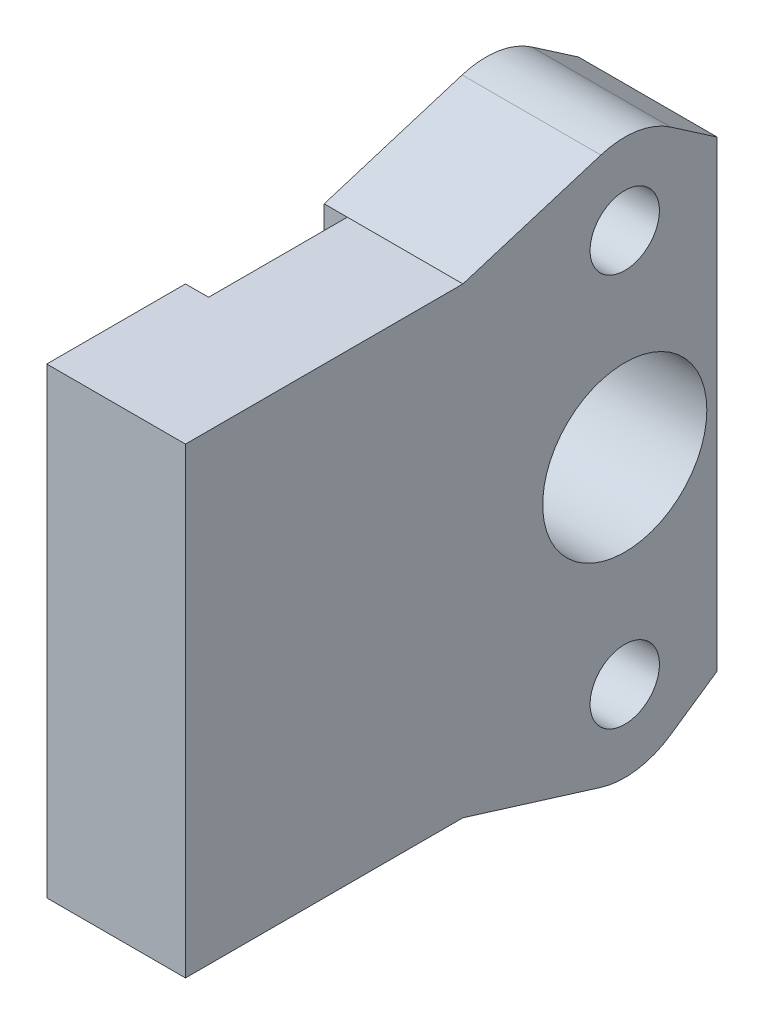
SolidWorks part; units mm, degrees
ref_plane "Front Plane" through (0, 0, 0) normal (0, 0, 1) x (1, 0, 0)
ref_plane "Top Plane" through (0, 0, 0) normal (0, 1, 0) x (1, 0, 0)
ref_plane "Right Plane" through (0, 0, 0) normal (1, 0, 0) x (0, 0, -1)
sketch "Sketch1" plane through (0, 0, 0) normal (1, 0, 0) x (0, 0, -1)
  line L0 (0, 8.5) -> (0, -8.5) construction
  line L1 (-7, 10) -> (-1.0334, 11.844)
  line L2 (1.9803, 11.3859) -> (4, 10)
  line L3 (-7, 10) -> (-19, 10)
  line L4 (-7, -10) -> (-1.0334, -11.844)
  line L5 (4, 10) -> (4, -10)
  line L6 (1.9803, -11.3859) -> (4, -10)
  line L7 (-19, 10) -> (-19, -10)
  line L8 (-19, -10) -> (-7, -10)
  circle A0 centre (0, 0) radius 12.55 construction
  circle A1 centre (0, 0) radius 3.55
  circle A2 centre (0, -8.5) radius 1.5
  circle A3 centre (0, 8.5) radius 1.5
  arc A4 (-1.0334, 11.844) -> (1.9803, 11.3859) centre (0, 8.5) cw
  arc A5 (-1.0334, -11.844) -> (1.9803, -11.3859) centre (0, -8.5) ccw
  dimension "D1" = 25.1
  dimension "D2" = 7.1
  dimension "D3" = 3
  dimension "D5" = 4
  dimension "D7" = 3.5
  dimension "D6" = 12
  dimension "D8" = 7
  dimension "D4" = 8.5
  dimension "D9" = 10
  dimension "D10" = 10
extrude "Boss-Extrude1" add sketch "Sketch1" along normal blind 6
sketch "Sketch2" plane through (0, 0, 0) normal (-1, 0, 0) x (0, 0, 1)
  line L0 (19, -10) -> (7, -10) construction
  line L1 (13, 10) -> (7, 10)
  line L2 (13, 10) -> (13, -10)
  line L3 (13, -10) -> (7, -10)
  line L4 (7, 10) -> (7, -10)
  line L5 (7, 10) -> (19, 10) construction
  dimension "D1" = 6
  dimension "D2" = 7
extrude "Cut-Extrude1" cut sketch "Sketch2" against normal blind 1
